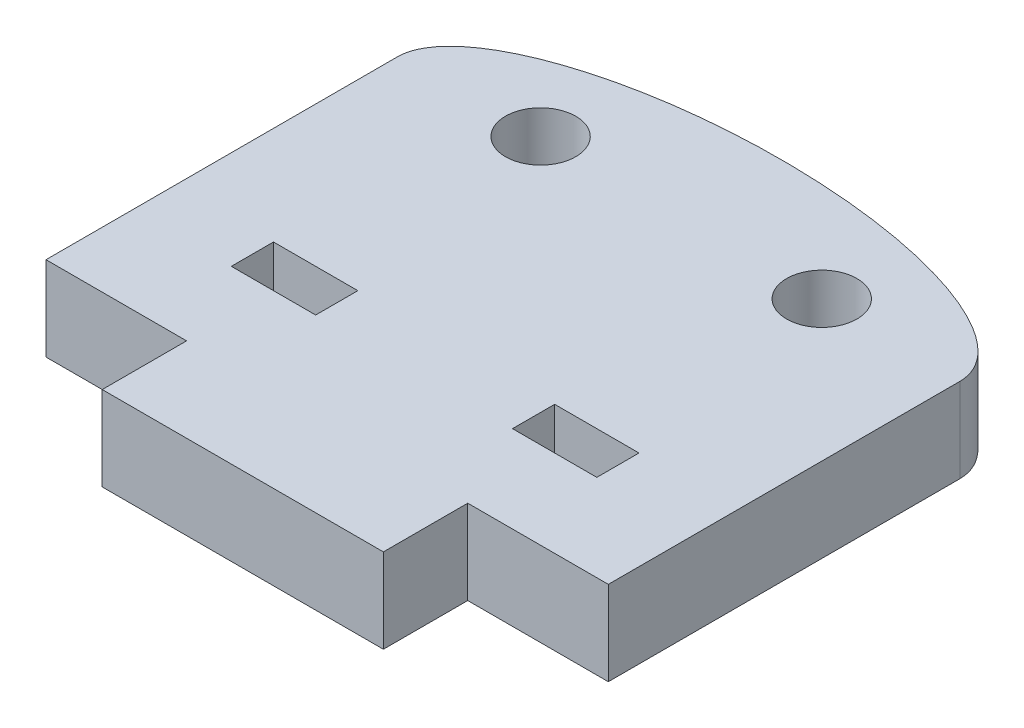
SolidWorks part; units mm, degrees
ref_plane "Front Plane" through (0, 0, 0) normal (0, 0, 1) x (1, 0, 0)
ref_plane "Top Plane" through (0, 0, 0) normal (0, 1, 0) x (1, 0, 0)
ref_plane "Right Plane" through (0, 0, 0) normal (1, 0, 0) x (0, 0, -1)
other "Configuration Table"
sketch "Sketch1" plane through (0, 0, 0) normal (0, 1, 0) x (1, 0, 0)
  line L0 (0, -25) -> (0, -17.5) construction
  line L6 (-3, -16) -> (3, -16)
  line L7 (-3, -16) -> (-3, -19)
  line L8 (-3, -19) -> (3, -19)
  line L9 (3, -16) -> (3, -19)
  line L10 (-3, -16) -> (3, -19) construction
  line L11 (-3, -19) -> (3, -16) construction
  line L17 (-10, -25.1828) -> (-10, -0.1828) construction
  line L19 (-30, -0.1828) -> (-30, -25.1828)
  line L21 (10, -0.1828) -> (10, -25.1828)
  line L22 (-20, -25) -> (-20, -17.5) construction
  line L23 (-23, -16) -> (-17, -16)
  line L24 (-23, -16) -> (-23, -19)
  line L25 (-23, -19) -> (-17, -19)
  line L26 (-17, -16) -> (-17, -19)
  line L27 (-23, -16) -> (-17, -19) construction
  line L28 (-23, -19) -> (-17, -16) construction
  line L29 (-30, -25.1828) -> (-20, -25.1828)
  line L31 (-20, -25.1828) -> (-20, -31.1828)
  line L32 (-20, -31.1828) -> (0, -31.1828)
  line L33 (0, -25.1828) -> (0, -31.1828)
  line L34 (0, -25.1828) -> (10, -25.1828)
  circle A0 centre (0, 0) radius 2.5
  circle A2 centre (-20, 0) radius 2.5
  ellipse E0 centre (-10, -0.1828) end of major axis (10, -0.1828) minor radius 7.3172 (-30, -0.1828) -> (10, -0.1828) cw
  dimension "D4" = 5
  dimension "D9" = 20
  dimension "D1" = 25
  dimension "D2" = 6
  dimension "D3" = 7.5
  dimension "D5" = 3
  dimension "D6" = 6
  dimension "D7" = 10
  dimension "D8" = 10
  dimension "D10" = 7.5
  dimension "D11" = 3
  dimension "D12" = 6
  dimension "D13" = 20
extrude "Boss-Extrude1" add sketch "Sketch1" along normal blind 6
